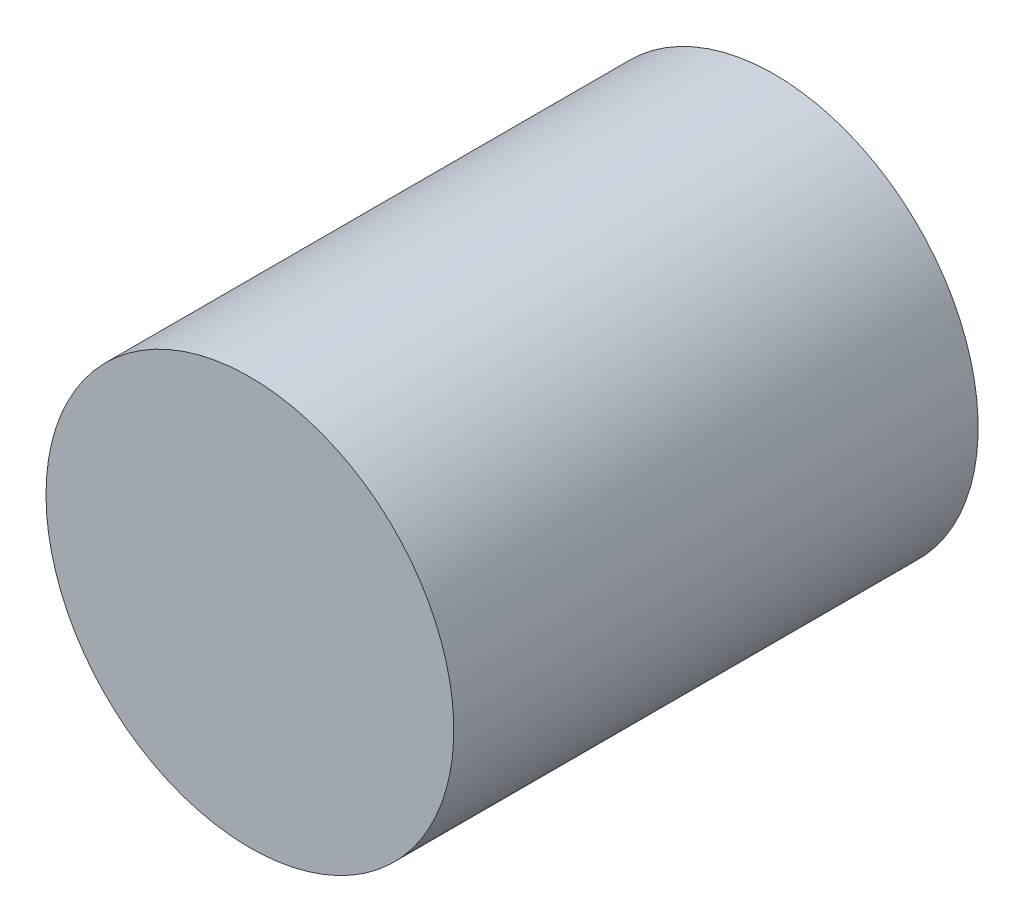
SolidWorks part; units mm, degrees
ref_plane "前视基准面" through (0, 0, 0) normal (0, 0, 1) x (1, 0, 0)
ref_plane "上视基准面" through (0, 0, 0) normal (0, 1, 0) x (1, 0, 0)
ref_plane "右视基准面" through (0, 0, 0) normal (1, 0, 0) x (0, 0, -1)
other "Configuration Table"
sketch "草图1" plane through (0, 0, 0) normal (0, 0, 1) x (1, 0, 0)
  circle A0 centre (0, 0) radius 35
extrude "solid_obs_01_elbow_cylinder" add sketch "草图1" along normal blind 90
